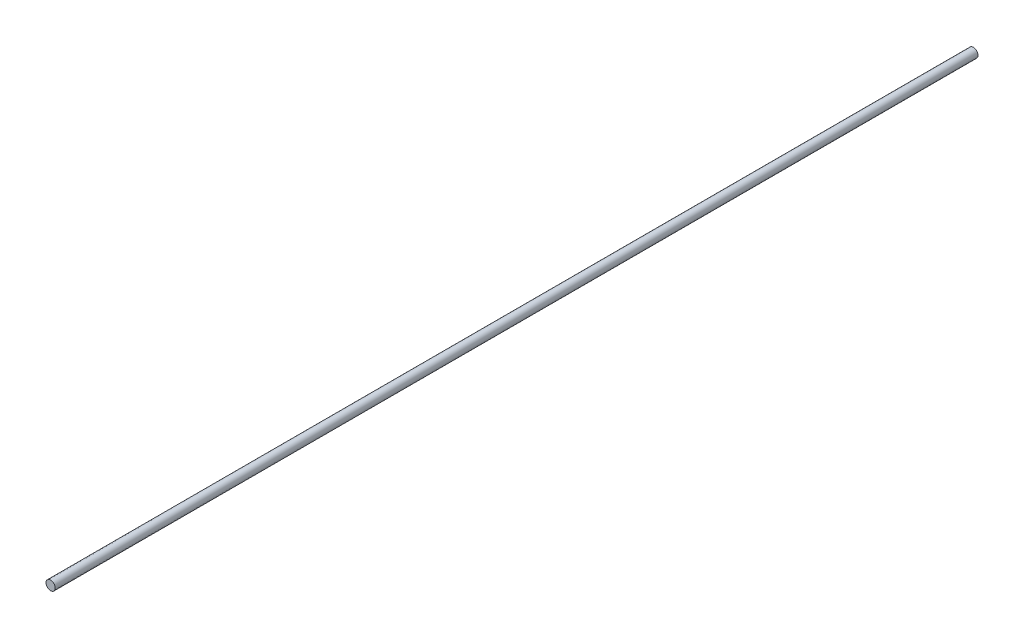
SolidWorks part; units mm, degrees
material "Plain Carbon Steel"
ref_plane "Front Plane" through (0, 0, 0) normal (0, 0, 1) x (1, 0, 0)
ref_plane "Top Plane" through (0, 0, 0) normal (0, 1, 0) x (1, 0, 0)
ref_plane "Right Plane" through (0, 0, 0) normal (1, 0, 0) x (0, 0, -1)
sketch "Sketch1" plane through (0, 0, 0) normal (0, 0, 1) x (1, 0, 0)
  circle A0 centre (0, 0) radius 4
  dimension "D1" = 8
extrude "Boss-Extrude1" add sketch "Sketch1" along normal blind 800
